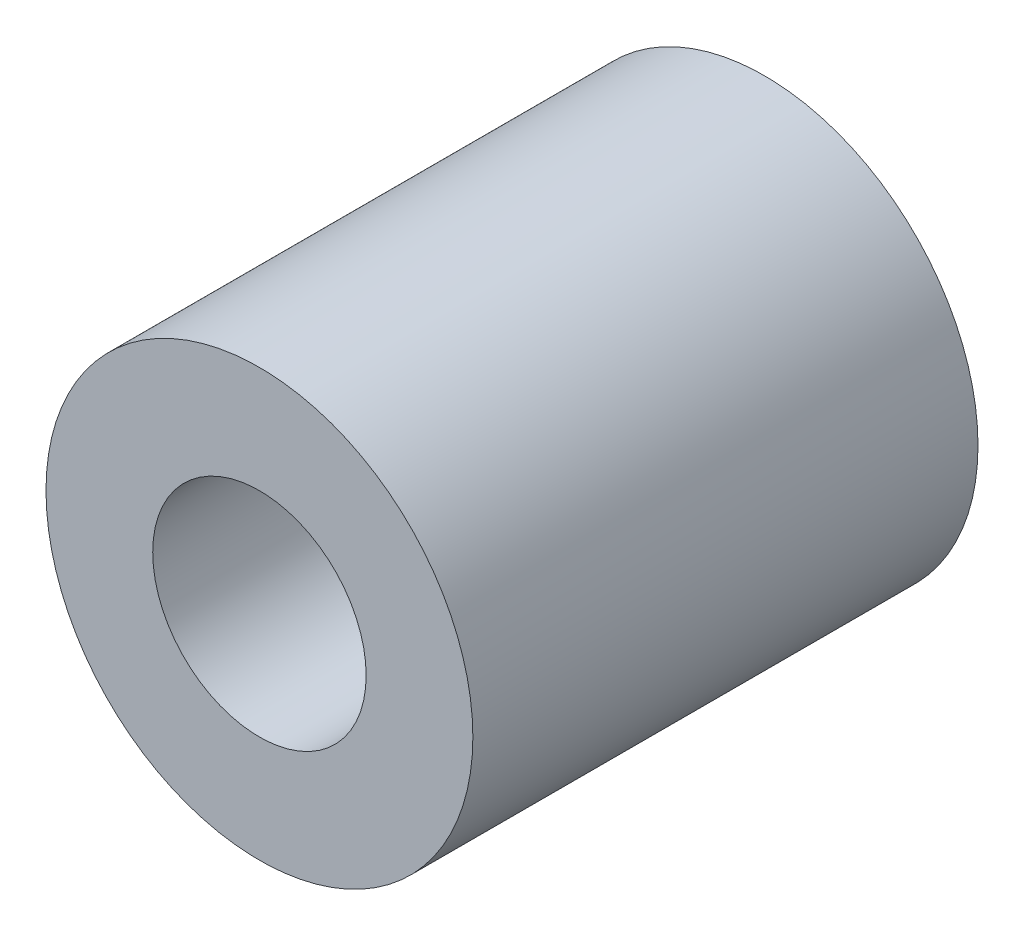
SolidWorks part; units mm, degrees
ref_plane "前视基准面" through (0, 0, 0) normal (0, 0, 1) x (1, 0, 0)
ref_plane "上视基准面" through (0, 0, 0) normal (0, 1, 0) x (1, 0, 0)
ref_plane "右视基准面" through (0, 0, 0) normal (1, 0, 0) x (0, 0, -1)
sketch "草图1" plane through (0, 0, 0) normal (0, 0, 1) x (1, 0, 0)
  circle A0 centre (0, 0) radius 4.5
  circle A1 centre (0, 0) radius 2.25
  dimension "D1" = 4.5
  dimension "D2" = 9
extrude "凸台-拉伸1" add sketch "草图1" along normal blind 10.65
